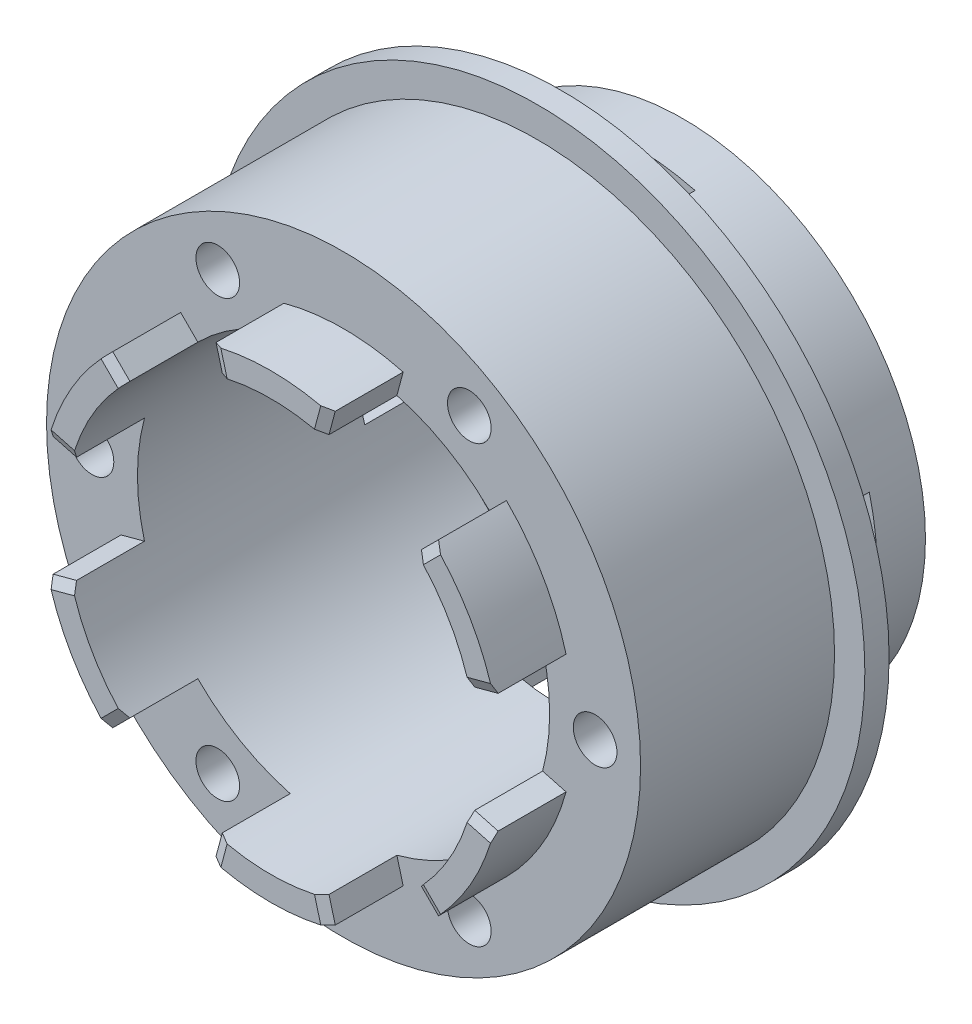
SolidWorks part; units mm, degrees
ref_plane "정면" through (0, 0, 0) normal (0, 0, 1) x (1, 0, 0)
ref_plane "윗면" through (0, 0, 0) normal (0, 1, 0) x (1, 0, 0)
ref_plane "우측면" through (0, 0, 0) normal (1, 0, 0) x (0, 0, -1)
sketch "스케치1" plane through (0, 0, 0) normal (0, 0, 1) x (1, 0, 0)
  circle A0 centre (0, 0) radius 10
  dimension "D1" = 20
extrude "보스-돌출1" add sketch "스케치1" along normal blind 2
sketch "스케치2" plane through (0, 0, 2) normal (0, 0, 1) x (1, 0, 0)
  circle A0 centre (0, 0) radius 10
  circle A1 centre (0, 0) radius 8.5
  circle A5 centre (0, 0) radius 10 construction
  dimension "D1" = 1.5
extrude "보스-돌출2" add sketch "스케치2" along normal blind 3
sketch "스케치4" plane through (0, 0, 5) normal (0, 0, 1) x (1, 0, 0)
  circle A0 centre (0, 0) radius 13.5
  circle A1 centre (0, 0) radius 8.5
  circle A2 centre (0, 0) radius 8.5 construction
  dimension "D1" = 27
extrude "보스-돌출3" add sketch "스케치4" along normal blind 1
sketch "스케치5" plane through (0, 0, 6) normal (0, 0, 1) x (1, 0, 0)
  circle A0 centre (0, 0) radius 8.5
  circle A1 centre (0, 0) radius 12.25
  circle A2 centre (0, 0) radius 8.5 construction
  dimension "D1" = 24.5
extrude "보스-돌출4" add sketch "스케치5" along normal blind 8
sketch "스케치6" plane through (0, 0, 14) normal (0, 0, 1) x (1, 0, 0)
  circle A0 centre (0, 0) radius 10.375 construction
  circle A6 centre (0, 0) radius 8.5 construction
  circle A8 centre (10.375, 0) radius 0.9
  circle A9 centre (5.1875, -8.985) radius 0.9
  circle A10 centre (-5.1875, -8.985) radius 0.9
  circle A11 centre (-10.375, 0) radius 0.9
  circle A12 centre (-5.1875, 8.985) radius 0.9
  circle A13 centre (5.1875, 8.985) radius 0.9
  point P19 (0, 0)
  point P20 (0, 0)
  dimension "D1" = 1.875
  dimension "D2" = 1.8
  dimension "D3" = 6
extrude "컷-돌출1" cut sketch "스케치6" against normal blind 8
sketch "스케치7" plane through (0, 0, 0) normal (0, 0, -1) x (-1, 0, 0)
  circle A0 centre (0, 0) radius 7 construction
  circle A5 centre (0, 0) radius 3
  circle A6 centre (-7, 0) radius 1.15
  circle A7 centre (7, 0) radius 1.15
  circle A9 centre (0, 7) radius 1.15
  circle A11 centre (0, -7) radius 1.15
  point P12 (0, -7)
  dimension "D1" = 14
  dimension "D2" = 2.3
  dimension "D4" = 6
extrude "컷-돌출2" cut sketch "스케치7" against normal through all
sketch "스케치8" plane through (0, 0, 0) normal (0, 1, 0) x (1, 0, 0)
  line L0 (10, 0) -> (-10, 0) construction
  line L1 (-2.5, -2) -> (2.5, -2)
  line L2 (-2.5, -2) -> (-2.5, -5)
  line L3 (-2.5, -5) -> (2.5, -5)
  line L4 (2.5, -2) -> (2.5, -5)
  line L5 (-2.5, -2) -> (2.5, -5) construction
  line L6 (-2.5, -5) -> (2.5, -2) construction
  line L8 (10, -5) -> (10, 0) construction
  line L9 (-10, 0) -> (-10, -5) construction
  line L10 (10, -5) -> (-10, -5) construction
  point P0 (0, -3.5)
  dimension "D1" = 2
  dimension "D3" = 7.5
  dimension "D4" = 7.5
extrude "컷-돌출3" cut sketch "스케치8" against normal through all both and the other way through all
sketch "스케치9" plane through (0, 0, 0) normal (1, 0, 0) x (0, 0, -1)
  line L0 (-5, -9.6825) -> (-5, 9.6825) construction
  line L1 (-5, -2.5) -> (-2, -2.5)
  line L2 (-5, -2.5) -> (-5, 2.5)
  line L3 (-5, 2.5) -> (-2, 2.5)
  line L4 (-2, -2.5) -> (-2, 2.5)
  line L5 (0, 10) -> (-2, 10) construction
  line L6 (-2, -10) -> (0, -10) construction
  line L7 (0, -10) -> (0, 10) construction
  dimension "D1" = 7.5
  dimension "D2" = 7.5
  dimension "D3" = 2
extrude "컷-돌출4" cut sketch "스케치9" against normal through all both and the other way through all
sketch "스케치10" plane through (0, 0, 14) normal (0, 0, 1) x (1, 0, 0)
  line L1 (2.2, 8.2104) -> (2.4588, 9.1763)
  line L3 (6.0104, 6.0104) -> (6.7175, 6.7175)
  line L5 (8.2104, 2.2) -> (9.1763, 2.4588)
  line L7 (8.2104, -2.2) -> (9.1763, -2.4588)
  line L9 (6.0104, -6.0104) -> (6.7175, -6.7175)
  line L11 (2.2, -8.2104) -> (2.4588, -9.1763)
  line L13 (-2.2, -8.2104) -> (-2.4588, -9.1763)
  line L15 (-6.0104, -6.0104) -> (-6.7175, -6.7175)
  line L17 (-8.2104, -2.2) -> (-9.1763, -2.4588)
  line L19 (-8.2104, 2.2) -> (-9.1763, 2.4588)
  line L21 (-6.0104, 6.0104) -> (-6.7175, 6.7175)
  line L23 (-2.2, 8.2104) -> (-2.4588, 9.1763)
  arc A0 (-6.7175, 6.7175) -> (-9.1763, 2.4588) centre (0, 0) ccw
  arc A1 (-8.2104, -2.2) -> (-6.0104, -6.0104) centre (0, 0) ccw
  arc A2 (2.4588, 9.1763) -> (-2.4588, 9.1763) centre (0, 0) ccw
  arc A3 (9.1763, 2.4588) -> (6.7175, 6.7175) centre (0, 0) ccw
  arc A4 (6.7175, -6.7175) -> (9.1763, -2.4588) centre (0, 0) ccw
  arc A5 (-2.4588, -9.1763) -> (2.4588, -9.1763) centre (0, 0) ccw
  arc A6 (-9.1763, -2.4588) -> (-6.7175, -6.7175) centre (0, 0) ccw
  arc A7 (-2.2, -8.2104) -> (2.2, -8.2104) centre (0, 0) ccw
  arc A8 (6.0104, -6.0104) -> (8.2104, -2.2) centre (0, 0) ccw
  arc A9 (8.2104, 2.2) -> (6.0104, 6.0104) centre (0, 0) ccw
  arc A10 (2.2, 8.2104) -> (-2.2, 8.2104) centre (0, 0) ccw
  arc A11 (-6.0104, 6.0104) -> (-8.2104, 2.2) centre (0, 0) ccw
  circle A12 centre (0, 0) radius 8.5 construction
  arc A13 (8.124, 2.5) -> (2.5, 8.124) centre (0, 0) ccw construction
  point P30 (0, 0)
  dimension "D1" = 1
extrude "보스-돌출5" add sketch "스케치10" along normal blind 3
chamfer "모따기1" distance 0.2 angle 64 12 edges at (-8.6933, -2.3294, 17) (-6.364, -6.364, 17) (-2.3294, -8.6933, 17) (2.3294, -8.6933, 17) (6.364, -6.364, 17) (8.6933, -2.3294, 17) (8.6933, 2.3294, 17) (6.364, 6.364, 17) (2.3294, 8.6933, 17) (-2.3294, 8.6933, 17) (-6.364, 6.364, 17) (-8.6933, 2.3294, 17)
